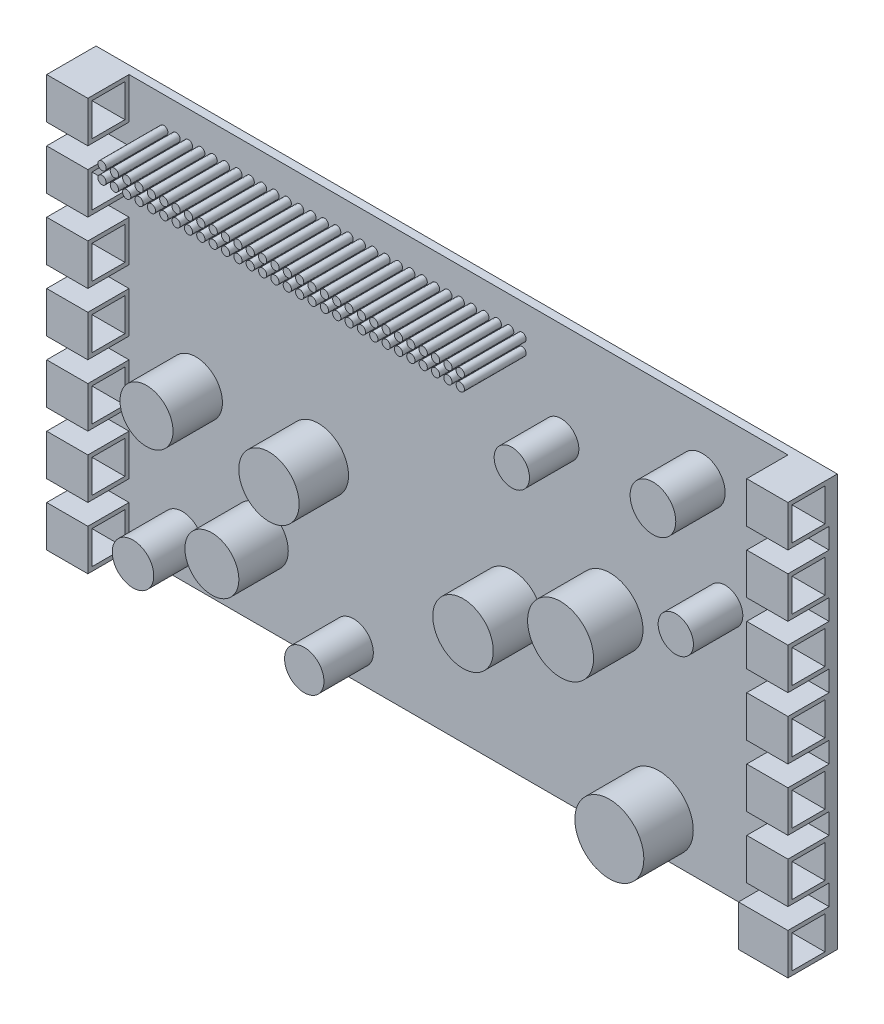
SolidWorks part; units mm, degrees
ref_plane "前视基准面" through (0, 0, 0) normal (0, 0, 1) x (1, 0, 0)
ref_plane "上视基准面" through (0, 0, 0) normal (0, 1, 0) x (1, 0, 0)
ref_plane "右视基准面" through (0, 0, 0) normal (1, 0, 0) x (0, 0, -1)
sketch "草图1" plane through (0, 0, 0) normal (0, 0, 1) x (1, 0, 0)
  line L1 (90, -50) -> (-90, -50)
  line L2 (90, -50) -> (90, 50)
  line L3 (90, 50) -> (-90, 50)
  line L4 (-90, -50) -> (-90, 50)
  line L5 (90, -50) -> (-90, 50) construction
  line L6 (90, 50) -> (-90, -50) construction
  point P0 (0, 0)
  dimension "D1" = 100
  dimension "D2" = 180
extrude "凸台-拉伸1" add sketch "草图1" along normal blind 2
sketch "草图4" plane through (90, 0, 0) normal (1, 0, 0) x (0, 0, -1)
  line L0 (-2, -50) -> (-12, -50)
  line L1 (-12, -50) -> (-12, -40)
  line L2 (-12, -40) -> (-2, -40)
  line L3 (-2, -50) -> (-2, 50) construction
  line L4 (-2, -40) -> (-2, -50)
  line L6 (-3, -41) -> (-11, -41)
  line L7 (-3, -41) -> (-3, -49)
  line L8 (-3, -49) -> (-11, -49)
  line L9 (-11, -41) -> (-11, -49)
  line L10 (-3, -41) -> (-11, -49) construction
  line L11 (-3, -49) -> (-11, -41) construction
  point P4 (-7, -45)
  dimension "D1" = 10
  dimension "D2" = 10
  dimension "D3" = 8
  dimension "D4" = 8
  dimension "D5" = 1
  dimension "D6" = 1
extrude "凸台-拉伸2" add sketch "草图4" against normal blind 10
sketch "草图5" plane through (80, 0, 0) normal (-1, 0, 0) x (0, 0, 1)
  line L4 (2, -40) -> (2, -50)
  line L5 (2, -50) -> (12, -50)
  line L6 (12, -50) -> (12, -40)
  line L7 (12, -40) -> (2, -40)
  line L8 (2, -40) -> (2, -50)
  line L9 (2, -50) -> (12, -50)
  line L10 (12, -50) -> (12, -40)
  line L11 (12, -40) -> (2, -40)
  dimension "D1" = 0
extrude "凸台-拉伸3" add sketch "草图5" along normal blind 2
pattern_linear "阵列(线性)1" count 7 spacing 15 along (0, 1, 0) of "凸台-拉伸2"
mirror "镜向1" about plane through (0, 0, 0) normal (1, 0, 0) of "阵列(线性)1", "凸台-拉伸2"
sketch "草图6" plane through (0, 0, 2) normal (0, 0, 1) x (1, 0, 0)
  circle A0 centre (-67.0353, -40.448) radius 5.0402
  circle A1 centre (-47.8823, -30.8715) radius 6.5523
  circle A2 centre (-25.4532, -41.9601) radius 4.7816
  circle A3 centre (-34.0217, -7.6864) radius 7.3257
  circle A4 centre (-63.7591, -7.6864) radius 6.4399
  circle A5 centre (13.1046, -15.0121) radius 7.3435
  circle A6 centre (24.9492, 25.8313) radius 4.2842
  circle A7 centre (36.7938, -4.4102) radius 8.0091
  circle A8 centre (48.6384, -40.448) radius 8.3773
  circle A9 centre (59.2229, 34.3997) radius 5.5443
  circle A10 centre (64.7672, 10.7105) radius 4.2842
extrude "凸台-拉伸4" add sketch "草图6" along normal blind 12
sketch "草图7" plane through (0, 0, 2) normal (0, 0, 1) x (1, 0, 0)
  circle A0 centre (-71.5658, 39.5316) radius 1
  circle A1 centre (-68.5658, 39.5316) radius 1
  circle A2 centre (-65.5658, 39.5316) radius 1
  circle A3 centre (-62.5658, 39.5316) radius 1
  circle A4 centre (-59.5658, 39.5316) radius 1
  circle A5 centre (-56.5658, 39.5316) radius 1
  circle A6 centre (-53.5658, 39.5316) radius 1
  circle A7 centre (-50.5658, 39.5316) radius 1
  circle A8 centre (-47.5658, 39.5316) radius 1
  circle A9 centre (-44.5658, 39.5316) radius 1
  circle A10 centre (-41.5658, 39.5316) radius 1
  circle A11 centre (-38.5658, 39.5316) radius 1
  circle A12 centre (-35.5658, 39.5316) radius 1
  circle A13 centre (-32.5658, 39.5316) radius 1
  circle A14 centre (-29.5658, 39.5316) radius 1
  circle A15 centre (-26.5658, 39.5316) radius 1
  circle A16 centre (-23.5658, 39.5316) radius 1
  circle A17 centre (-20.5658, 39.5316) radius 1
  circle A18 centre (-17.5658, 39.5316) radius 1
  circle A19 centre (-14.5658, 39.5316) radius 1
  circle A20 centre (-11.5658, 39.5316) radius 1
  circle A21 centre (-8.5658, 39.5316) radius 1
  circle A22 centre (-5.5658, 39.5316) radius 1
  circle A23 centre (-2.5658, 39.5316) radius 1
  circle A24 centre (0.4342, 39.5316) radius 1
  circle A25 centre (3.4342, 39.5316) radius 1
  circle A26 centre (6.4342, 39.5316) radius 1
  circle A27 centre (9.4342, 39.5316) radius 1
  circle A28 centre (12.4342, 39.5316) radius 1
  circle A29 centre (15.4342, 39.5316) radius 1
  circle A30 centre (-68.5658, 42.5316) radius 1
  circle A31 centre (-65.5658, 42.5316) radius 1
  circle A32 centre (-62.5658, 42.5316) radius 1
  circle A33 centre (-59.5658, 42.5316) radius 1
  circle A34 centre (-56.5658, 42.5316) radius 1
  circle A35 centre (-53.5658, 42.5316) radius 1
  circle A36 centre (-50.5658, 42.5316) radius 1
  circle A37 centre (-47.5658, 42.5316) radius 1
  circle A38 centre (-44.5658, 42.5316) radius 1
  circle A39 centre (-41.5658, 42.5316) radius 1
  circle A40 centre (-38.5658, 42.5316) radius 1
  circle A41 centre (-35.5658, 42.5316) radius 1
  circle A42 centre (-32.5658, 42.5316) radius 1
  circle A43 centre (-29.5658, 42.5316) radius 1
  circle A44 centre (-26.5658, 42.5316) radius 1
  circle A45 centre (-23.5658, 42.5316) radius 1
  circle A46 centre (-20.5658, 42.5316) radius 1
  circle A47 centre (-17.5658, 42.5316) radius 1
  circle A48 centre (-14.5658, 42.5316) radius 1
  circle A49 centre (-11.5658, 42.5316) radius 1
  circle A50 centre (-8.5658, 42.5316) radius 1
  circle A51 centre (-5.5658, 42.5316) radius 1
  circle A52 centre (-2.5658, 42.5316) radius 1
  circle A53 centre (0.4342, 42.5316) radius 1
  circle A54 centre (3.4342, 42.5316) radius 1
  circle A55 centre (6.4342, 42.5316) radius 1
  circle A56 centre (9.4342, 42.5316) radius 1
  circle A57 centre (12.4342, 42.5316) radius 1
  circle A58 centre (15.4342, 42.5316) radius 1
  circle A59 centre (-71.5658, 42.5316) radius 1
  dimension "D1" = 2
  dimension "D2" = 30
  dimension "D3" = 2
extrude "凸台-拉伸5" add sketch "草图7" along normal blind 15
scale "缩放比例1" scale about centroid uniform scaling yes scale factor 0.5
